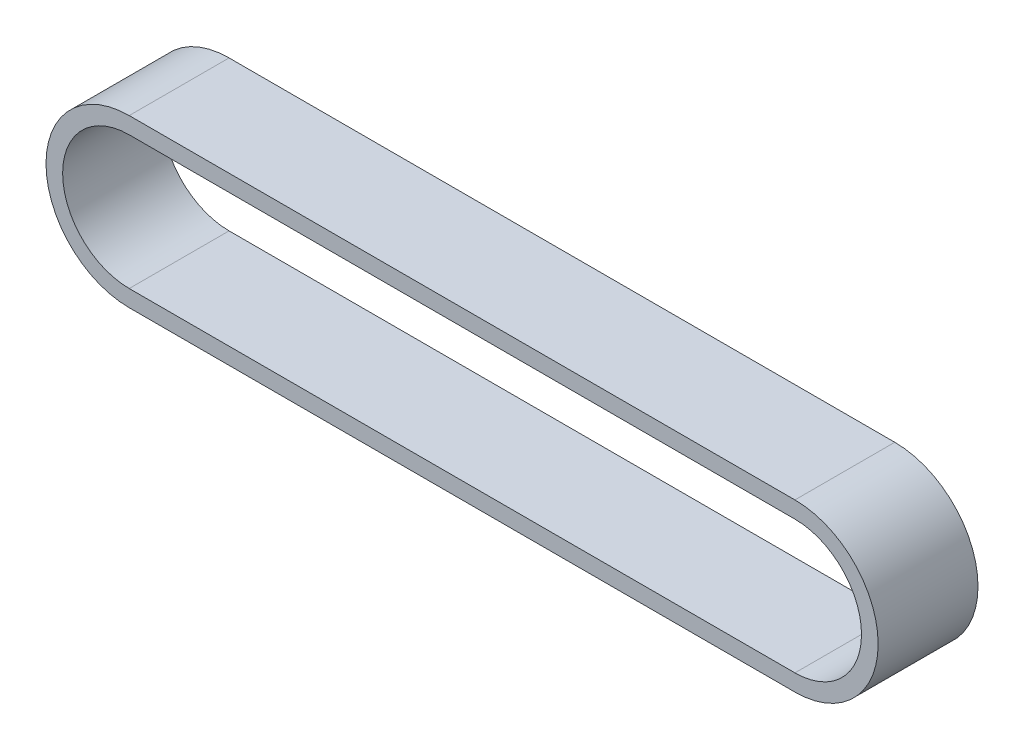
SolidWorks part; units mm, degrees
ref_plane "Front Plane" through (0, 0, 0) normal (0, 0, 1) x (1, 0, 0)
ref_plane "Top Plane" through (0, 0, 0) normal (0, 1, 0) x (1, 0, 0)
ref_plane "Right Plane" through (0, 0, 0) normal (1, 0, 0) x (0, 0, -1)
sketch "Sketch1" plane through (0, 0, 0) normal (0, 0, 1) x (1, 0, 0)
  line L0 (0.5886, 58.8403) -> (102.1886, 58.8403) construction
  line L1 (0.5886, 69.0003) -> (102.1886, 69.0003)
  line L2 (0.5886, 48.6803) -> (102.1886, 48.6803)
  line L3 (0.5886, 58.8403) -> (102.1886, 58.8403) construction
  line L4 (0.5886, 71.5403) -> (102.1886, 71.5403)
  line L5 (0.5886, 46.1403) -> (102.1886, 46.1403)
  line L6 (102.1886, 69.0003) -> (0.5886, 69.0003) construction
  line L7 (-22.2714, 71.5403) -> (125.0486, 71.5403) construction
  arc A0 (0.5886, 69.0003) -> (0.5886, 48.6803) centre (0.5886, 58.8403) ccw
  arc A1 (102.1886, 48.6803) -> (102.1886, 69.0003) centre (102.1886, 58.8403) ccw
  arc A2 (0.5886, 71.5403) -> (0.5886, 46.1403) centre (0.5886, 58.8403) ccw
  arc A3 (102.1886, 46.1403) -> (102.1886, 71.5403) centre (102.1886, 58.8403) ccw
  point P4 (51.3886, 58.8403)
  point P9 (51.3886, 58.8403)
extrude "Boss-Extrude1" add sketch "Sketch1" along normal blind 15.24
